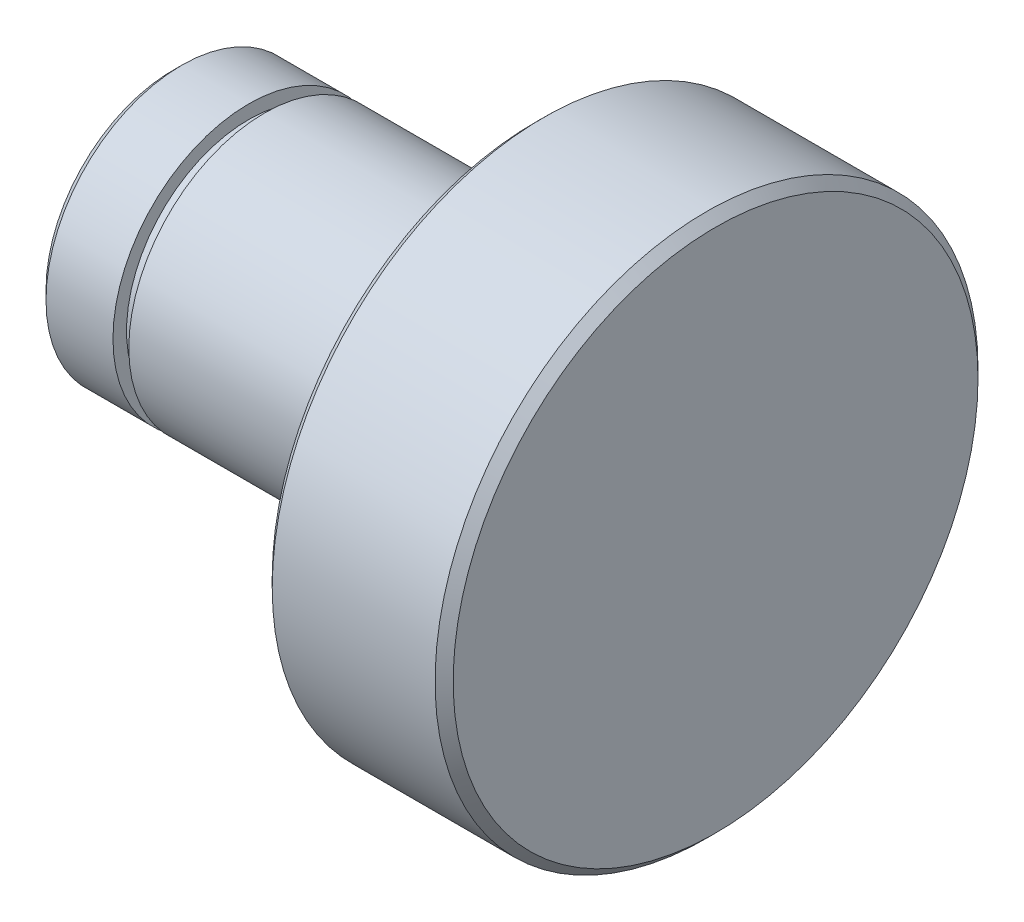
SolidWorks part; units mm, degrees
ref_plane "Piano frontale" through (0, 0, 0) normal (0, 0, 1) x (1, 0, 0)
ref_plane "Piano superiore" through (0, 0, 0) normal (0, 1, 0) x (1, 0, 0)
ref_plane "Piano destro" through (0, 0, 0) normal (1, 0, 0) x (0, 0, -1)
sketch "Schizzo1" plane through (0, 0, 0) normal (0, 0, 1) x (1, 0, 0)
  line L0 (0, 0) -> (-86.9148, 0) construction
  line L1 (0, 0) -> (0, 30)
  line L2 (0, 30) -> (-20, 30)
  line L3 (-20, 30) -> (-20, 15)
  line L4 (-20, 15) -> (-60, 15)
  line L5 (-60, 15) -> (-60, 0)
  line L6 (-60, 0) -> (0, 0)
  dimension "D1" = 30
  dimension "D2" = 60
  dimension "D3" = 20
  dimension "D4" = 40
revolve "Rivoluzione1" add sketch "Schizzo1" angle 360 about L0
chamfer "Smusso1" distance 1 angle 45 3 edges at (0, 0, -30) (-20, 0, -30) (-60, 0, -15)
sketch "Schizzo5" plane through (0, 0, 0) normal (0, 0, 1) x (1, 0, 0)
  line L1 (-50, 17.6709) -> (-51.6, 17.6709)
  line L2 (-50, 17.6709) -> (-50, 13.5)
  line L3 (-50, 13.5) -> (-51.6, 13.5)
  line L4 (-51.6, 17.6709) -> (-51.6, 13.5)
  line L5 (0, 0) -> (-78.8805, 0) construction
  line L6 (-50, 13.5) -> (-49.85, 13.5)
  line L7 (-50, 13.5) -> (-50, 17.6709)
  line L8 (-50, 17.6709) -> (-49.85, 17.6709)
  line L9 (-49.85, 13.5) -> (-49.85, 17.6709)
  line L10 (-20, 29) -> (-20, -29) construction
  point P11 (0, 0)
  point P12 (0, 0)
  dimension "D1" = 1.6
  dimension "D2" = 1.75
  dimension "D3" = 27
  dimension "D4" = 31.6
revolve "Taglia-Rivoluzione7" cut sketch "Schizzo5" angle 360 about L5
